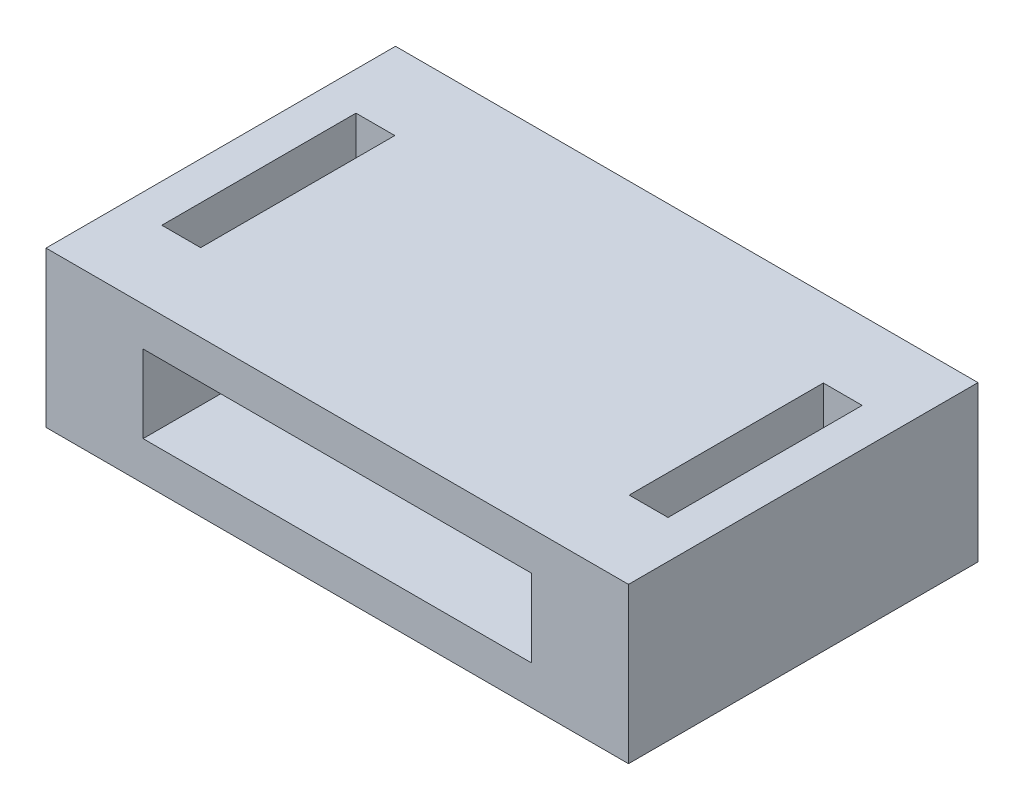
SolidWorks part; units mm, degrees
ref_plane "Front Plane" through (0, 0, 0) normal (0, 0, 1) x (1, 0, 0)
ref_plane "Top Plane" through (0, 0, 0) normal (0, 1, 0) x (1, 0, 0)
ref_plane "Right Plane" through (0, 0, 0) normal (1, 0, 0) x (0, 0, -1)
sketch "Sketch1" plane through (0, 0, 0) normal (0, 1, 0) x (1, 0, 0)
  line L0 (-19.05, 0) -> (-15.2849, 0) construction
  line L1 (-19.05, -11.43) -> (19.05, -11.43)
  line L2 (-19.05, -11.43) -> (-19.05, 11.43)
  line L3 (-19.05, 11.43) -> (19.05, 11.43)
  line L4 (19.05, -11.43) -> (19.05, 11.43)
  line L5 (-19.05, -11.43) -> (19.05, 11.43) construction
  line L6 (-19.05, 11.43) -> (19.05, -11.43) construction
  line L7 (0, -1000) -> (0, 49000) construction
  line L8 (-14.0149, -6.35) -> (-16.5549, -6.35)
  line L9 (-14.0149, -6.35) -> (-14.0149, 6.35)
  line L10 (-14.0149, 6.35) -> (-16.5549, 6.35)
  line L11 (-16.5549, -6.35) -> (-16.5549, 6.35)
  line L12 (-14.0149, -6.35) -> (-16.5549, 6.35) construction
  line L13 (-14.0149, 6.35) -> (-16.5549, -6.35) construction
  line L14 (14.0149, 6.35) -> (16.5549, 6.35)
  line L15 (16.5549, -6.35) -> (16.5549, 6.35)
  line L16 (14.0149, -6.35) -> (16.5549, -6.35)
  line L17 (14.0149, -6.35) -> (14.0149, 6.35)
  point P0 (0, 0)
  dimension "D1" = 22.86
  dimension "D2" = 38.1
  dimension "D3" = 12.7
  dimension "D4" = 2.54
  dimension "D5" = 2.4951
extrude "Boss-Extrude2" add sketch "Sketch1" along normal blind 2.54
sketch "Sketch3" plane through (0, 2.54, 0) normal (0, 1, 0) x (1, 0, 0)
  line L0 (0, 11.43) -> (0, 2.54) construction
  line L1 (19.05, 11.43) -> (-19.05, 11.43) construction
  line L2 (5.3189, 2.54) -> (-5.3189, 2.54) construction
  circle A0 centre (-5.3189, 2.54) radius 1.016
  circle A1 centre (5.3189, 2.54) radius 1.016
extrude "Boss-Extrude3" add sketch "Sketch3" along normal blind 5.08
ref_plane "Plane2" through (0, 7.62, 0) normal (0, 1, 0) x (1, 0, 0)
sketch "Sketch4" plane through (0, 7.62, 0) normal (0, 1, 0) x (1, 0, 0)
  line L0 (14.0149, 6.35) -> (14.0149, -6.35) construction
  line L1 (-19.05, 11.43) -> (19.05, 11.43)
  line L2 (-19.05, 11.43) -> (-19.05, -11.43)
  line L3 (-19.05, -11.43) -> (19.05, -11.43)
  line L4 (19.05, 11.43) -> (19.05, -11.43)
  line L5 (-16.5549, 6.35) -> (-14.0149, 6.35)
  line L6 (-16.5549, 6.35) -> (-16.5549, -6.35)
  line L7 (-16.5549, -6.35) -> (-14.0149, -6.35)
  line L8 (-14.0149, 6.35) -> (-14.0149, -6.35)
  line L9 (14.0149, 6.35) -> (16.5549, 6.35)
  line L10 (14.0149, 6.35) -> (14.0149, -6.35)
  line L11 (14.0149, -6.35) -> (16.5549, -6.35)
  line L12 (16.5549, 6.35) -> (16.5549, -6.35)
sketch "Sketch5" plane through (0, 2.54, 0) normal (0, 1, 0) x (1, 0, 0)
  line L0 (-19.05, -11.43) -> (-19.05, 11.43)
  line L1 (19.05, 11.43) -> (-19.05, 11.43) construction
  line L2 (-19.05, 11.43) -> (-19.05, -11.43) construction
  line L3 (-19.05, 11.43) -> (19.05, 11.43)
  line L4 (19.05, 11.43) -> (19.05, -11.43)
  line L5 (-19.05, -11.43) -> (19.05, -11.43) construction
  line L6 (19.05, -11.43) -> (12.7, -11.43)
  line L7 (12.7, -11.43) -> (12.7, 6.35)
  line L8 (-19.05, -11.43) -> (-12.7, -11.43)
  line L9 (-12.7, -11.43) -> (-12.7, 6.35)
  line L10 (-12.7, 6.35) -> (12.7, 6.35)
extrude "Boss-Extrude5" add sketch "Sketch5" along normal blind 5.08
sketch "Sketch6" plane through (0, 7.62, 0) normal (0, 1, 0) x (1, 0, 0)
  line L1 (-16.5549, 6.35) -> (-14.0149, 6.35)
  line L2 (-16.5549, 6.35) -> (-16.5549, -6.35)
  line L3 (-16.5549, -6.35) -> (-14.0149, -6.35)
  line L4 (-14.0149, 6.35) -> (-14.0149, -6.35)
  line L5 (14.0149, 6.35) -> (16.5549, 6.35)
  line L6 (14.0149, 6.35) -> (14.0149, -6.35)
  line L7 (14.0149, -6.35) -> (16.5549, -6.35)
  line L8 (16.5549, 6.35) -> (16.5549, -6.35)
extrude "Cut-Extrude1" cut sketch "Sketch6" against normal through all
extrude "Boss-Extrude6" add sketch "Sketch4" along normal blind 2.54
